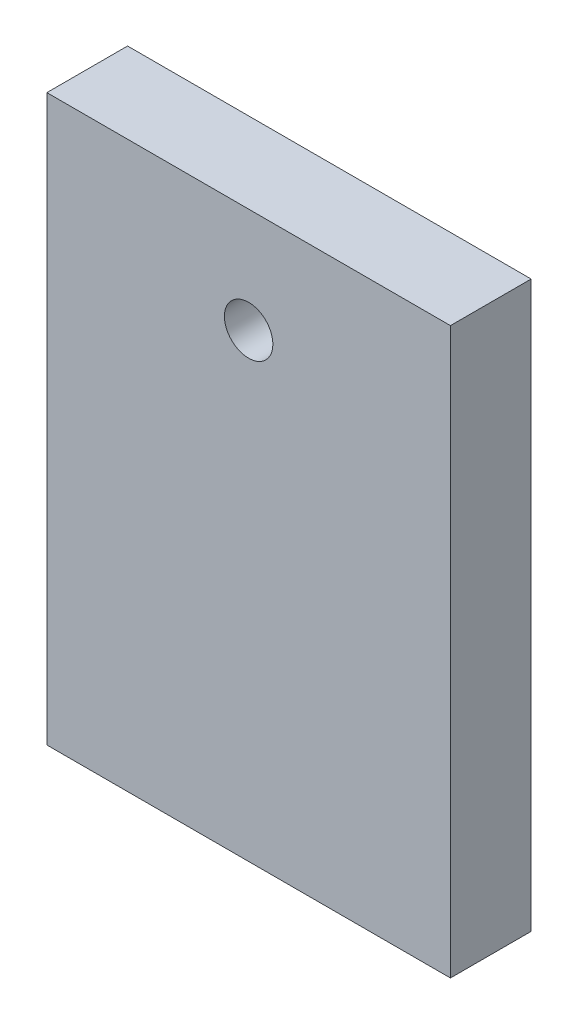
SolidWorks part; units mm, degrees
ref_plane "Front Plane" through (0, 0, 0) normal (0, 0, 1) x (1, 0, 0)
ref_plane "Top Plane" through (0, 0, 0) normal (0, 1, 0) x (1, 0, 0)
ref_plane "Right Plane" through (0, 0, 0) normal (1, 0, 0) x (0, 0, -1)
sketch "Sketch2" plane through (0, 0, 0) normal (0, 0, 1) x (1, 0, 0)
  line L1 (-12.5, -17.5) -> (12.5, -17.5)
  line L2 (-12.5, -17.5) -> (-12.5, 17.5)
  line L3 (-12.5, 17.5) -> (12.5, 17.5)
  line L4 (12.5, -17.5) -> (12.5, 17.5)
  line L5 (-12.5, -17.5) -> (12.5, 17.5) construction
  line L6 (-12.5, 17.5) -> (12.5, -17.5) construction
  point P0 (0, 0)
  dimension "D1" = 25
  dimension "D2" = 35
extrude "Boss-Extrude1" add sketch "Sketch2" along normal blind 5
sketch "Sketch3" plane through (0, 0, 5) normal (0, 0, 1) x (1, 0, 0)
  line L0 (0, -17.5) -> (0, -7.5) construction
  line L1 (0, -7.5) -> (0, 11) construction
  line L2 (-12.5, -17.5) -> (12.5, -17.5) construction
  circle A0 centre (0, 11) radius 1.5
  dimension "D3" = 3
  dimension "D1" = 10
  dimension "D2" = 18.5
extrude "Cut-Extrude1" cut sketch "Sketch3" against normal through all
